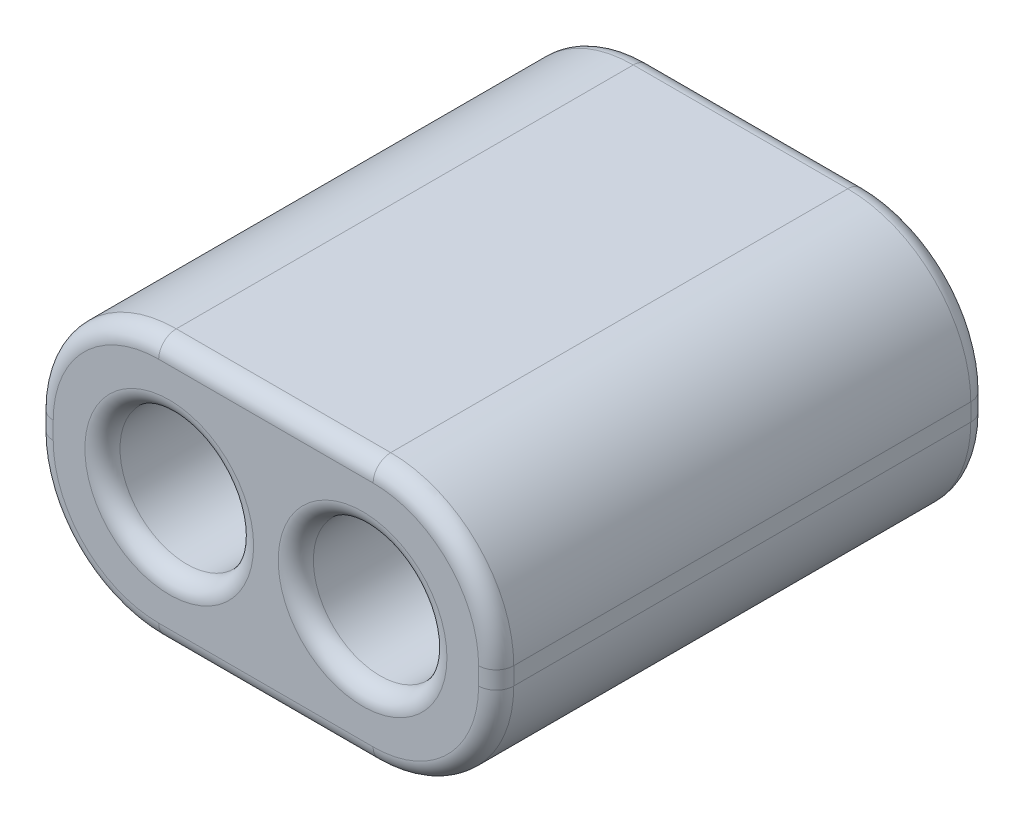
SolidWorks part; units mm, degrees
ref_plane "Спереди" through (0, 0, 0) normal (0, 0, 1) x (1, 0, 0)
ref_plane "Сверху" through (0, 0, 0) normal (0, 1, 0) x (1, 0, 0)
ref_plane "Справа" through (0, 0, 0) normal (1, 0, 0) x (0, 0, -1)
other "Configuration Table"
sketch "Эскиз1" plane through (0, 0, 0) normal (0, 0, 1) x (1, 0, 0)
  line L0 (-15.5203, 0) -> (12.0506, 0) construction
  line L1 (-6.55, 3.75) -> (6.55, 3.75)
  line L2 (-6.55, 3.75) -> (-6.55, -3.75)
  line L3 (-6.55, -3.75) -> (6.55, -3.75)
  line L4 (6.55, 3.75) -> (6.55, -3.75)
  line L5 (-6.55, 3.75) -> (6.55, -3.75) construction
  line L6 (-6.55, -3.75) -> (6.55, 3.75) construction
  line L7 (-2.75, 8.7418) -> (-2.75, -11.0605) construction
  line L8 (2.75, 8.7418) -> (2.75, -11.0605) construction
  circle A0 centre (-2.75, 0) radius 1.9
  circle A1 centre (2.75, 0) radius 1.9
  point P0 (0, 0)
  dimension "D5" = 3.8
  dimension "D6" = 3.8
  dimension "D1" = 13.1
  dimension "D2" = 7.5
  dimension "D3" = 3.8
  dimension "D4" = 3.8
extrude "Бобышка-Вытянуть1" add sketch "Эскиз1" along normal blind 14
fillet "Скругление1" radius 3.5 4 edges at (6.55, -3.75, 7) (-6.55, -3.75, 7) (-6.55, 3.75, 7) (6.55, 3.75, 7)
fillet "Скругление2" radius 0.5 10 edges at (4.65, 0, 14) (-5.5249, -2.7249, 14) (-6.55, 0, 14) (-5.5249, 2.7249, 14) (0, 3.75, 14) (5.5249, 2.7249, 14) (6.55, 0, 14) (5.5249, -2.7249, 14) (0, -3.75, 14) (-0.85, 0, 14)
fillet "Скругление3" radius 0.5 10 edges at (4.65, 0, 0) (-0.85, 0, 0) (5.5249, 2.7249, 0) (0, 3.75, 0) (-5.5249, 2.7249, 0) (-6.55, 0, 0) (-5.5249, -2.7249, 0) (0, -3.75, 0) (5.5249, -2.7249, 0) (6.55, 0, 0)
